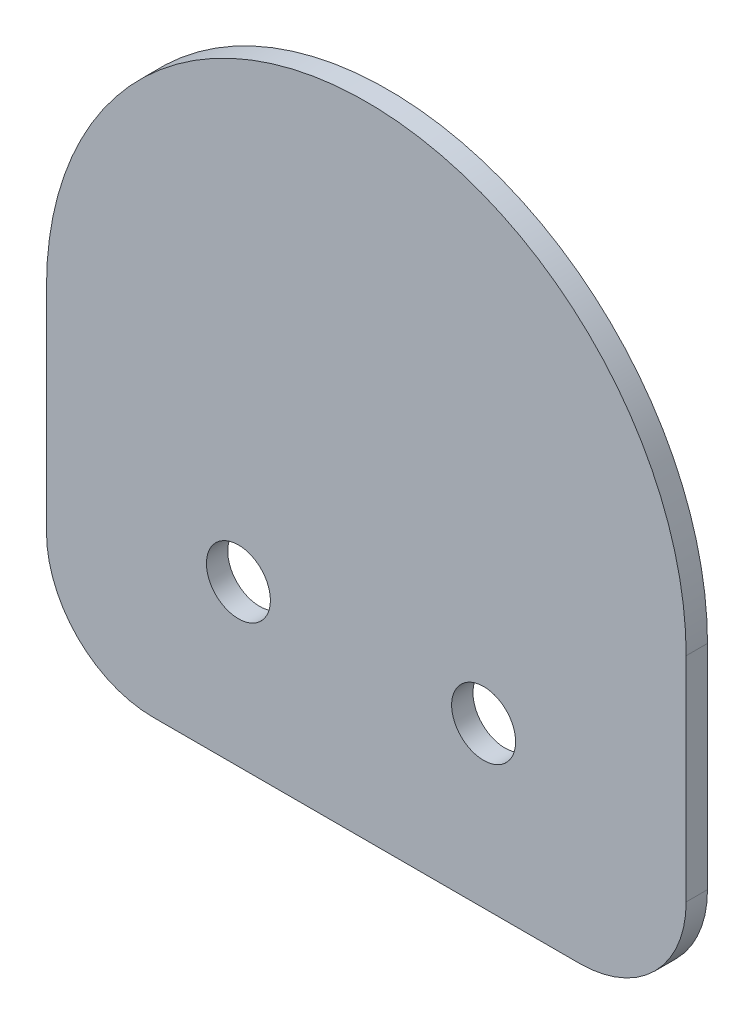
SolidWorks part; units mm, degrees
ref_plane "Front Plane" through (0, 0, 0) normal (0, 0, 1) x (1, 0, 0)
ref_plane "Top Plane" through (0, 0, 0) normal (0, 1, 0) x (1, 0, 0)
ref_plane "Right Plane" through (0, 0, 0) normal (1, 0, 0) x (0, 0, -1)
sketch "Sketch1" plane through (0, 0, 0) normal (0, 0, 1) x (1, 0, 0)
  line L1 (-23.7725, 48.4877) -> (6.2275, 48.4877)
  line L2 (-23.7725, 48.4877) -> (-23.7725, 63.4877)
  line L4 (6.2275, 48.4877) -> (6.2275, 63.4877)
  arc A0 (-23.7725, 63.4877) -> (6.2275, 63.4877) centre (-8.7725, 63.4877) cw
  circle A1 centre (-14.7725, 55.9877) radius 1.5
  circle A2 centre (-3.2725, 55.9877) radius 1.5
  dimension "D1" = 15
extrude "Boss-Extrude1" add sketch "Sketch1" along normal blind 1
fillet "Fillet2" radius 5 1 edges at (-23.7725, 48.4877, 0.5)
fillet "Fillet3" radius 5 1 edges at (6.2275, 48.4877, 0.5)
